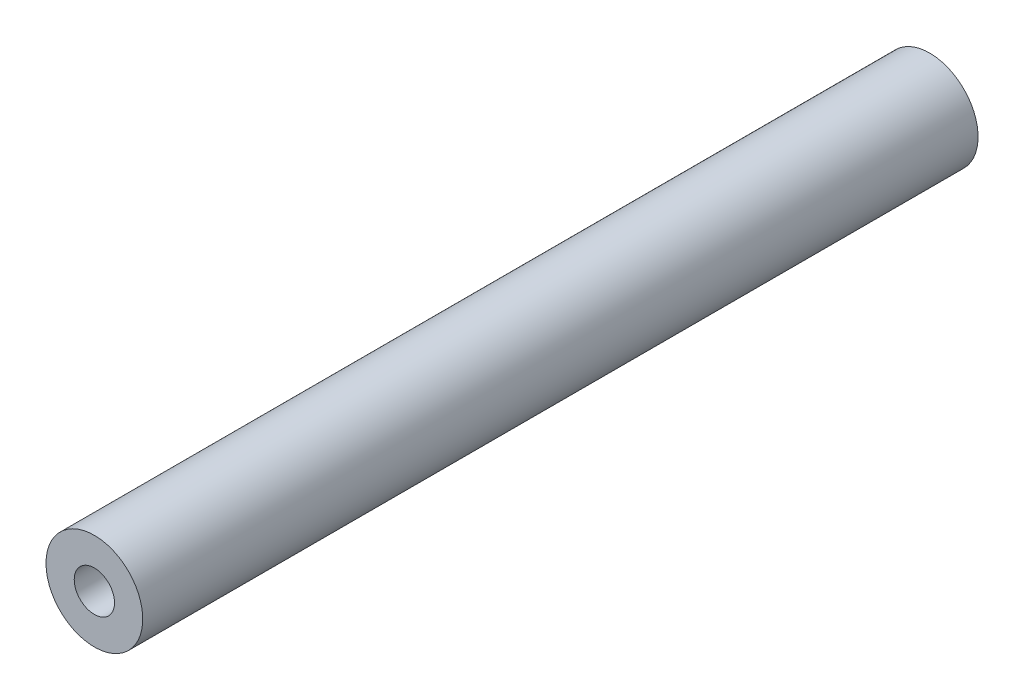
SolidWorks part; units mm, degrees
ref_plane "Plano frontal" through (0, 0, 0) normal (0, 0, 1) x (1, 0, 0)
ref_plane "Plano superior" through (0, 0, 0) normal (0, 1, 0) x (1, 0, 0)
ref_plane "Plano direito" through (0, 0, 0) normal (1, 0, 0) x (0, 0, -1)
sketch "Esboço1" plane through (0, 0, 0) normal (0, 0, 1) x (1, 0, 0)
  circle A0 centre (0, 0) radius 3
  circle A1 centre (0, 0) radius 1.25
  dimension "D1" = 2.5
  dimension "D2" = 6
extrude "Ressalto-extrusão1" add sketch "Esboço1" along normal blind 51.8
